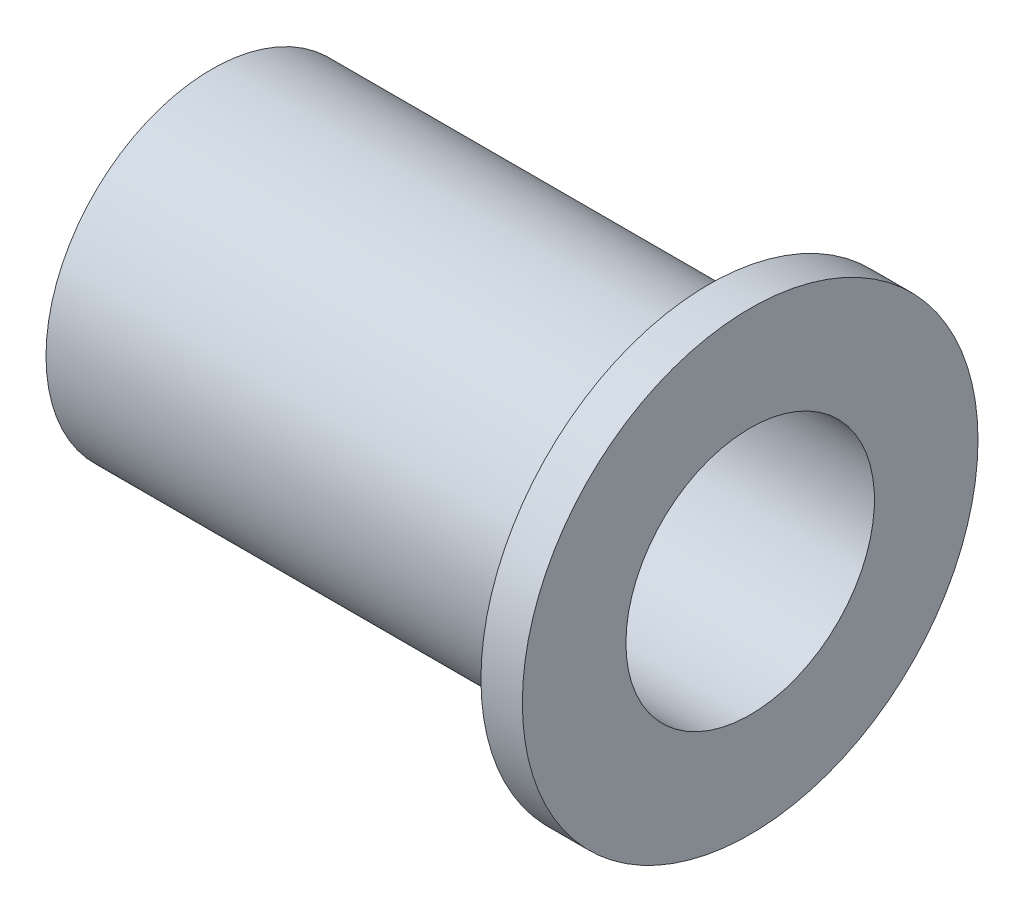
SolidWorks part; units mm, degrees
material "Brass"
ref_plane "Front Plane" through (0, 0, 0) normal (0, 0, 1) x (1, 0, 0)
ref_plane "Top Plane" through (0, 0, 0) normal (0, 1, 0) x (1, 0, 0)
ref_plane "Right Plane" through (0, 0, 0) normal (1, 0, 0) x (0, 0, -1)
sketch "Sketch1" plane through (0, 0, 0) normal (0, 1, 0) x (1, 0, 0)
  line L0 (0, 0) -> (105.1884, 0) construction
  line L1 (0, 4.7625) -> (0, 6.35)
  line L2 (0, 6.35) -> (19.05, 6.35)
  line L3 (19.05, 6.35) -> (19.05, 8.7312)
  line L4 (19.05, 8.7312) -> (20.6375, 8.7312)
  line L5 (20.6375, 8.7312) -> (20.6375, 4.7625)
  line L6 (20.6375, 4.7625) -> (0, 4.7625)
  dimension "D1" = 9.525
  dimension "D2" = 12.7
  dimension "D3" = 19.05
  dimension "D4" = 1.5875
  dimension "D5" = 17.4625
revolve "Revolve1" add sketch "Sketch1" angle 360 about L0
